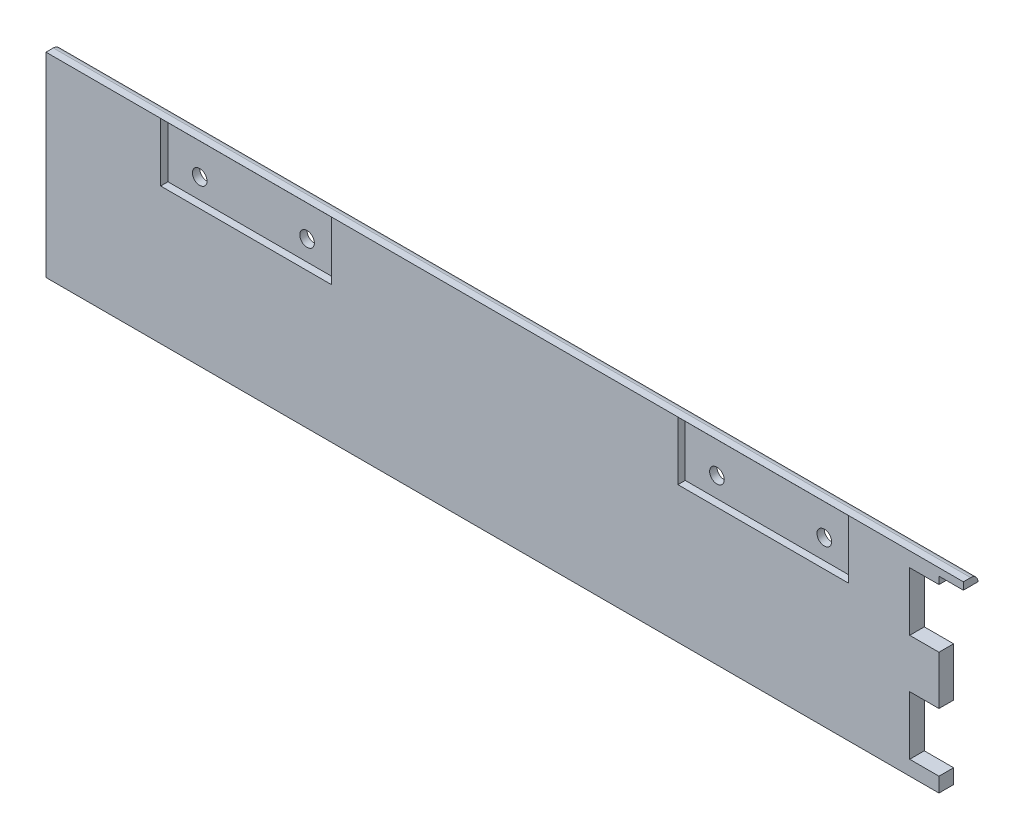
SolidWorks part; units mm, degrees
ref_plane "Plan de face" through (0, 0, 0) normal (0, 0, 1) x (1, 0, 0)
ref_plane "Plan de dessus" through (0, 0, 0) normal (0, 1, 0) x (1, 0, 0)
ref_plane "Plan de droite" through (0, 0, 0) normal (1, 0, 0) x (0, 0, -1)
sketch "Esquisse1" plane through (0, 0, 0) normal (0, 0, 1) x (1, 0, 0)
  line L1 (0, 0) -> (188, 0)
  line L2 (0, 0) -> (0, 40)
  line L3 (0, 40) -> (188, 40)
  line L4 (188, 0) -> (188, 40)
  dimension "D1" = 188
  dimension "D2" = 40
extrude "Boss.-Extru.1" add sketch "Esquisse1" along normal blind 3
fillet "Congé3" radius 1.5 1 edges at (94, 40, 0)
sketch "Esquisse3" plane through (0, 0, 0) normal (0, 0, -1) x (-1, 0, 0)
  line L0 (0, 0) -> (-188, 0) construction
  line L1 (-177, 37) -> (-183, 37)
  line L2 (-177, 37) -> (-177, 25)
  line L3 (-177, 25) -> (-183, 25)
  line L4 (-183, 25) -> (-183, 15)
  line L5 (-177, 15) -> (-183, 15)
  line L6 (-177, 15) -> (-177, 3)
  line L7 (-177, 3) -> (-183, 3)
  line L8 (-183, 37) -> (-183, 38.5)
  line L10 (0, 38.5) -> (-188, 38.5) construction
  line L11 (-183, 3) -> (-183, 0)
  line L13 (-183, 38.5) -> (-188, 38.5)
  line L14 (-188, 38.5) -> (-188, 0)
  line L15 (-188, 0) -> (-183, 0)
  dimension "D1" = 12
  dimension "D2" = 12
  dimension "D3" = 10
  dimension "D4" = 3
  dimension "D5" = 6
  dimension "D6" = 6
  dimension "D8" = 5
  dimension "D9" = 5
extrude "Enlèv. mat.-Extru.1" cut sketch "Esquisse3" against normal through all
sketch "Esquisse5" plane through (0, 0, 3) normal (0, 0, 1) x (1, 0, 0)
  line L0 (188, 38.5) -> (188, 40) construction
  line L1 (129.5, 27.99) -> (164.5, 27.99)
  line L2 (129.5, 27.99) -> (129.5, 39.99)
  line L3 (129.5, 39.99) -> (164.5, 39.99)
  line L4 (164.5, 27.99) -> (164.5, 39.99)
  line L5 (23.5, 27.99) -> (58.5, 27.99)
  line L6 (23.5, 27.99) -> (23.5, 39.99)
  line L7 (23.5, 39.99) -> (58.5, 39.99)
  line L8 (58.5, 27.99) -> (58.5, 39.99)
  line L9 (0, 40) -> (0, 0) construction
  line L10 (188, 40) -> (0, 40) construction
  dimension "D1" = 35
  dimension "D2" = 35
  dimension "D3" = 23.5
  dimension "D4" = 23.5
  dimension "D5" = 12
  dimension "D6" = 12
  dimension "D7" = 0.01
  dimension "D8" = 0.01
extrude "Enlèv. mat.-Extru.2" cut sketch "Esquisse5" against normal blind 1.5
sketch "Esquisse7" plane through (0, 0, 1.5) normal (0, 0, 1) x (1, 0, 0)
  line L0 (23.5, 39.99) -> (23.5, 27.99) construction
  line L1 (23.5, 27.99) -> (58.5, 27.99) construction
  circle A0 centre (30, 32.1) radius 1.5
  circle A1 centre (52, 32.1) radius 1.5
  dimension "D1" = 3
  dimension "D2" = 3
  dimension "D3" = 22
  dimension "D4" = 6.5
  dimension "D5" = 4.11
extrude "Enlèv. mat.-Extru.3" cut sketch "Esquisse7" against normal blind 1.5
sketch "Esquisse8" plane through (0, 0, 1.5) normal (0, 0, 1) x (1, 0, 0)
  line L0 (129.5, 27.99) -> (164.5, 27.99) construction
  line L1 (129.5, 39.99) -> (129.5, 27.99) construction
  circle A0 centre (136, 32.1) radius 1.5
  circle A1 centre (158, 32.1) radius 1.5
  dimension "D1" = 3
  dimension "D2" = 3
  dimension "D3" = 22
  dimension "D4" = 4.11
  dimension "D5" = 6.5
extrude "Enlèv. mat.-Extru.4" cut sketch "Esquisse8" against normal blind 1.5
